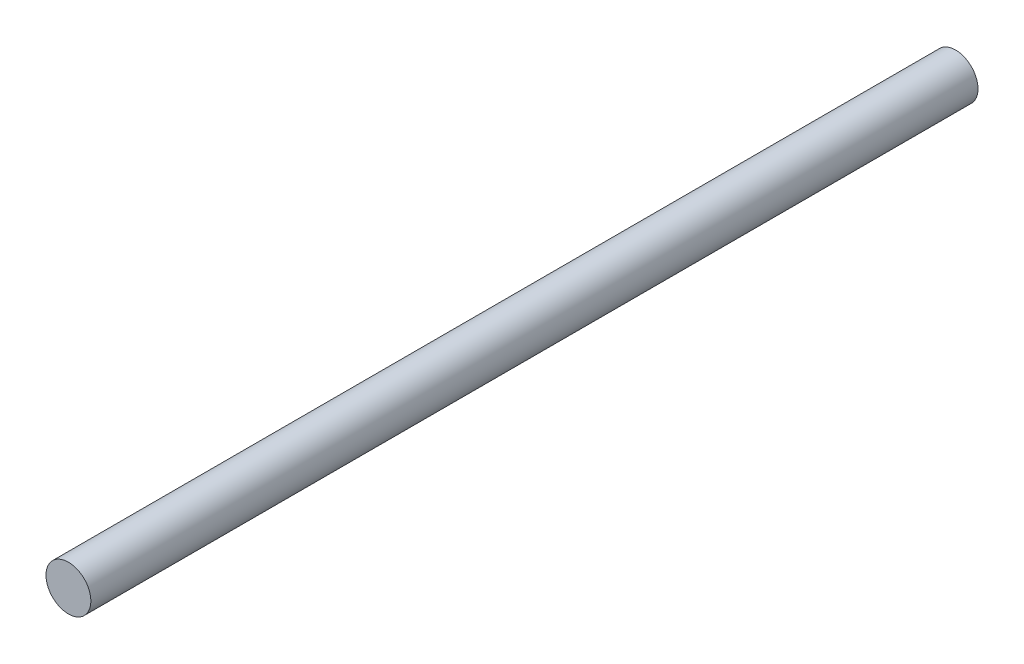
SolidWorks part; units mm, degrees
ref_plane "Front" through (0, 0, 0) normal (0, 0, 1) x (1, 0, 0)
ref_plane "Top" through (0, 0, 0) normal (0, 1, 0) x (1, 0, 0)
ref_plane "Right" through (0, 0, 0) normal (1, 0, 0) x (0, 0, -1)
sketch "Sketch1" plane through (0, 0, 0) normal (0, 0, 1) x (1, 0, 0)
  circle A0 centre (0, 0) radius 1.5875
  dimension "D1" = 3.175
extrude "Boss-Extrude1" add sketch "Sketch1" along normal blind 62.738
